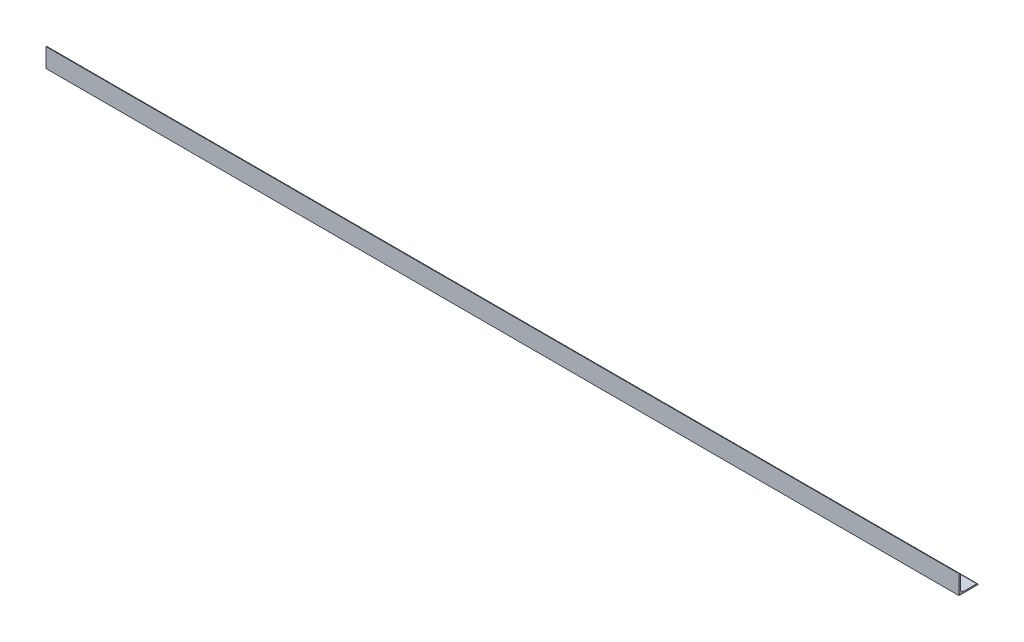
SolidWorks part; units mm, degrees
ref_plane "Front Plane" through (0, 0, 0) normal (0, 0, 1) x (1, 0, 0)
ref_plane "Top Plane" through (0, 0, 0) normal (0, 1, 0) x (1, 0, 0)
ref_plane "Right Plane" through (0, 0, 0) normal (1, 0, 0) x (0, 0, -1)
sketch "Sketch1" plane through (0, 0, 0) normal (0, 1, 0) x (1, 0, 0)
  line L0 (0, 0) -> (1920, 0)
  dimension "D1" = 1920
other "L angle (equal) 40X40X3(2)"
ref_plane "Plane1" through (0, 0, 0) normal (1, 0, 0) x (0, 0, -1)
sketch "Sketch13" plane through (0, 0, 0) normal (1, 0, 0) x (0, 0, -1)
  line L0 (0, 40) -> (0, 0)
  line L2 (3, 37) -> (3, 9)
  line L3 (9, 3) -> (37, 3)
  line L5 (40, 0) -> (0, 0)
  arc A0 (3, 37) -> (0, 40) centre (0, 37) ccw
  arc A1 (40, 0) -> (37, 3) centre (37, 0) ccw
  arc A2 (9, 3) -> (3, 9) centre (9, 9) cw
  point P8 (0, 20)
  point P9 (20, 0)
  point P10 (0, 0)
  dimension "Radius_2" = 3
  dimension "Radius_1" = 6
  dimension "V_leg" = 40
  dimension "H_leg" = 40
  dimension "thickness" = 3
ref_plane "Plane2" through (0, 0, 0) normal (0, -1, 0) x (-1, 0, 0)
sketch "Sketch15" plane through (0, 0, 0) normal (0, -1, 0) x (-1, 0, 0)
  line L0 (-960, 0) -> (-960, 40) construction
  line L4 (0, 0) -> (0, 40)
  line L5 (0, 40) -> (-1920, 40)
  line L6 (-1920, 40) -> (-1920, 0)
  line L7 (-1920, 0) -> (0, 0)
  line L12 (0, 0) -> (0, 40) construction
  line L13 (0, 40) -> (-1920, 40) construction
  line L14 (-1920, 40) -> (-1920, 0) construction
  line L15 (-1920, 0) -> (0, 0) construction
  circle A0 centre (-960, 20) radius 2
  circle A1 centre (-470, 20) radius 2
  circle A2 centre (-1450, 20) radius 2
  dimension "D2" = 2
  dimension "D1" = 0
  dimension "D3" = 2
extrude "Cut-Extrude1" cut sketch "Sketch15" against normal blind 10
ref_plane "Plane3" through (0, 0, 0) normal (0, 0.7071, 0.7071) x (-1, 0, 0)
